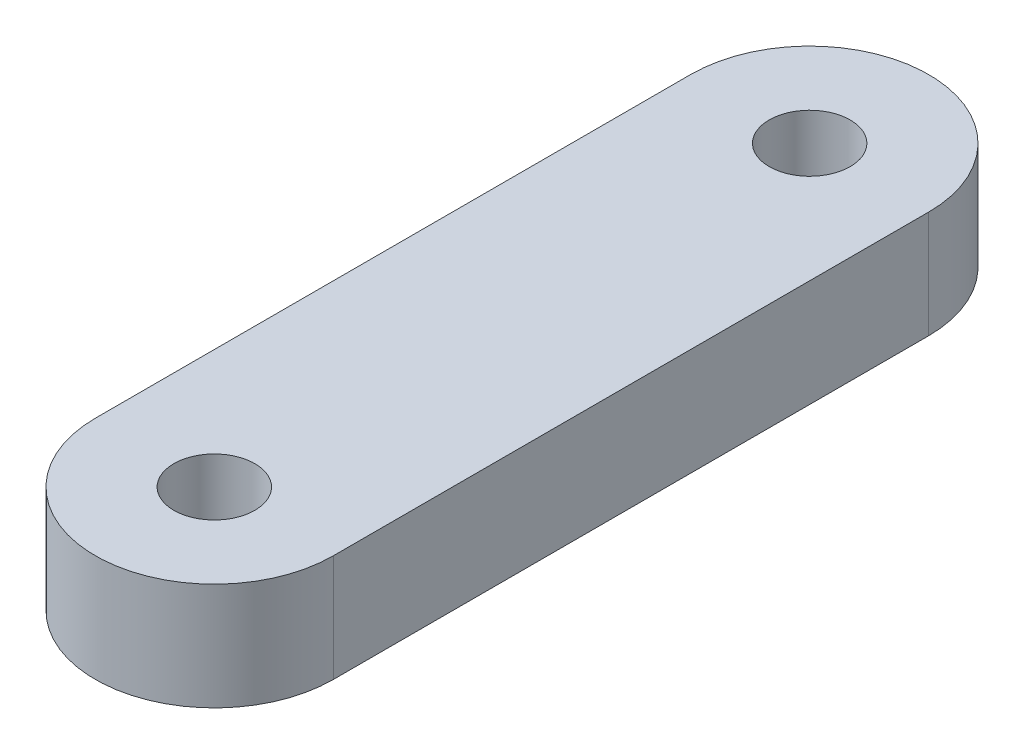
SolidWorks part; units mm, degrees
ref_plane "Front Plane" through (0, 0, 0) normal (0, 0, 1) x (1, 0, 0)
ref_plane "Top Plane" through (0, 0, 0) normal (0, 1, 0) x (1, 0, 0)
ref_plane "Right Plane" through (0, 0, 0) normal (1, 0, 0) x (0, 0, -1)
sketch "Sketch1" plane through (0, 0, 0) normal (0, 1, 0) x (1, 0, 0)
  line L0 (0, 0) -> (0, 25) construction
  line L1 (-5, 0) -> (-5, 25)
  line L2 (5, 0) -> (5, 25)
  arc A0 (-5, 0) -> (5, 0) centre (0, 0) ccw
  arc A1 (5, 25) -> (-5, 25) centre (0, 25) ccw
  circle A2 centre (0, 0) radius 1.7
  circle A3 centre (0, 25) radius 1.7
  point P3 (0, 12.5)
  dimension "D1" = 5
  dimension "D2" = 3.4
  dimension "D3" = 3.4
  dimension "D4" = 25
extrude "Boss-Extrude1" add sketch "Sketch1" along normal blind 4.5
